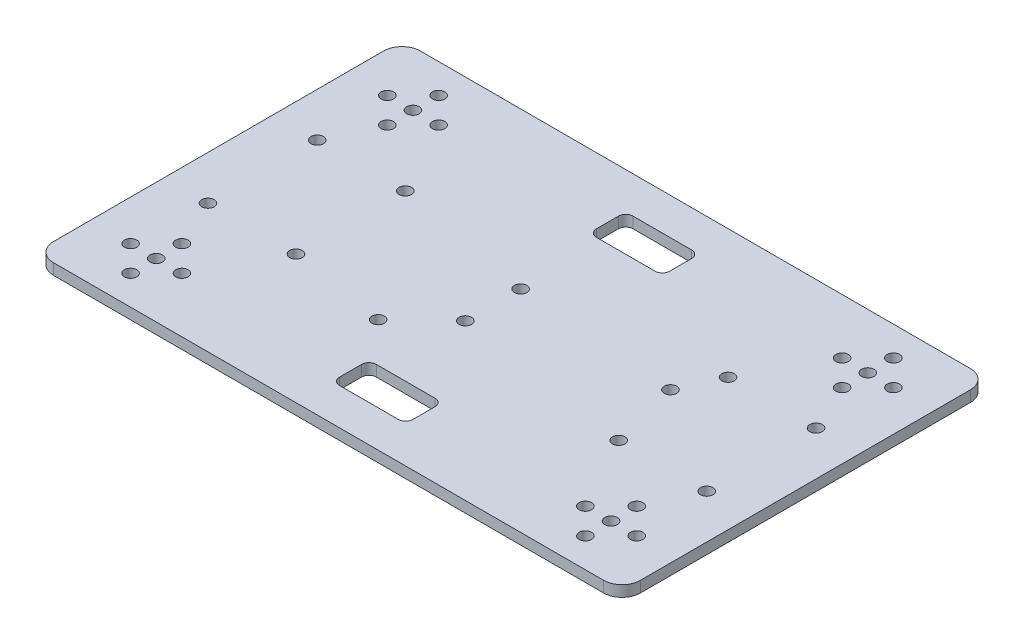
SolidWorks part; units mm, degrees
ref_plane "Front Plane" through (0, 0, 0) normal (0, 0, 1) x (1, 0, 0)
ref_plane "Top Plane" through (0, 0, 0) normal (0, 1, 0) x (1, 0, 0)
ref_plane "Right Plane" through (0, 0, 0) normal (1, 0, 0) x (0, 0, -1)
sketch "Sketch1" plane through (0, 0, 0) normal (0, 1, 0) x (1, 0, 0)
  line L1 (-80, -50) -> (80, -50)
  line L2 (-80, -50) -> (-80, 50)
  line L3 (-80, 50) -> (80, 50)
  line L4 (80, -50) -> (80, 50)
  line L5 (-80, -50) -> (80, 50) construction
  line L6 (-80, 50) -> (80, -50) construction
  point P0 (0, 0)
  dimension "D1" = 100
  dimension "D2" = 160
extrude "Boss-Extrude1" add sketch "Sketch1" along normal blind 3
sketch "Sketch3" plane through (0, 3, 0) normal (0, 1, 0) x (1, 0, 0)
  circle A0 centre (-68, 14.9) radius 1.5
  circle A1 centre (-44, 14.9) radius 1.5
  circle A2 centre (-68, -14.9) radius 1.5
  circle A3 centre (-44, -14.9) radius 1.5
  circle A4 centre (44, 14.9) radius 1.5
  circle A5 centre (68, 14.9) radius 1.5
  circle A6 centre (44, -14.9) radius 1.5
  circle A7 centre (68, -14.9) radius 1.5
  dimension "D1" = 3
  dimension "D2" = 3
  dimension "D3" = 3
  dimension "D4" = 3
  dimension "D5" = 3
  dimension "D6" = 3
  dimension "D7" = 3
  dimension "D8" = 3
hole_wizard "M3 Clearance Hole1" positions "3DSketch1" profile "Sketch4" hole size "M3" standard "ISO" end condition up to next
sketch3d "3DSketch1"
  point P0 (-68, 3, -14.9)
  point P3 (-44, 3, -14.9)
  point P6 (-68, 3, 14.9)
  point P9 (-44, 3, 14.9)
  point P12 (68, 3, -14.9)
  point P15 (44, 3, -14.9)
  point P18 (44, 3, 14.9)
  point P21 (68, 3, 14.9)
sketch "Sketch4" plane through (-68, 3, -14.9) normal (1, 0, 0) x (0, 0, 1)
  line L0 (0, 0) -> (0, 3)
  line L1 (0, 3) -> (1.7, 3)
  line L2 (1.7, 3) -> (1.7, 0)
  line L5 (1.7, 0) -> (0, 0)
  line L11 (0, -6.35) -> (0, 107.95) construction
  dimension "Thru Hole Dia." = 3.4
  dimension "Thru Hole Depth" = 3
sketch "Sketch8" plane through (0, 3, 0) normal (0, 1, 0) x (1, 0, 0)
  line L5 (-9, -30) -> (11, -30)
  line L6 (-9, -30) -> (-9, -40)
  line L7 (-9, -40) -> (11, -40)
  line L8 (11, -30) -> (11, -40)
  line L9 (-9, -30) -> (11, -40) construction
  line L10 (-9, -40) -> (11, -30) construction
  line L11 (-80, -50) -> (80, -50) construction
  line L12 (47, -22) -> (47, -48) construction
  line L13 (-80, 0) -> (80, 0) construction
  line L14 (-80, 50) -> (-80, -50) construction
  line L15 (80, -50) -> (80, 50) construction
  line L16 (-9, 40) -> (11, 30) construction
  line L17 (-9, 30) -> (11, 40) construction
  line L18 (11, 30) -> (11, 40)
  line L19 (-9, 40) -> (11, 40)
  line L20 (-9, 30) -> (-9, 40)
  line L21 (-9, 30) -> (11, 30)
  point P4 (1, -35)
  point P19 (1, 35)
  dimension "D1" = 20
  dimension "D2" = 10
  dimension "D3" = 10
  dimension "D4" = 46
extrude "Cut-Extrude1" cut sketch "Sketch8" against normal up to next
hole_wizard "M3 Clearance Hole3" positions "Sketch9" profile "Sketch10" hole size "M3" standard "ISO" end condition up to next
sketch "Sketch9" plane through (0, 3, 0) normal (0, 1, 0) x (1, 0, 0)
  point P0 (-5.121, 7.4767)
  point P3 (-5.1439, -7.5842)
sketch "Sketch10" plane through (-5.121, 3, -7.4767) normal (1, 0, 0) x (0, 0, 1)
  line L0 (0, 0) -> (0, 3)
  line L1 (0, 3) -> (1.7, 3)
  line L2 (1.7, 3) -> (1.7, 0)
  line L5 (1.7, 0) -> (0, 0)
  line L11 (0, -6.35) -> (0, 107.95) construction
  dimension "Thru Hole Dia." = 3.4
  dimension "Thru Hole Depth" = 3
hole_wizard "M3 Clearance Hole4" positions "Sketch11" profile "Sketch12" hole size "M3" standard "ISO" end condition up to next
sketch "Sketch11" plane through (0, 3, 0) normal (0, 1, 0) x (1, 0, 0)
  point P0 (-62, 35)
  point P3 (-62, 42)
  point P6 (-69, 35)
  point P9 (-62, 28)
  point P12 (-55, 35)
  point P15 (-62, -42)
  point P18 (-69, -35)
  point P21 (-62, -28)
  point P24 (-55, -35)
  point P27 (-62, -35)
  point P30 (-17.3, -19.2)
  point P33 (39.1, 4.1)
  point P36 (-5.121, 7.4767)
  point P39 (-5.1439, -7.5842)
  point P42 (62, -35)
  point P45 (69, -35)
  point P48 (62, -42)
  point P51 (55, -35)
  point P54 (62, -28)
  point P57 (69, 35)
  point P60 (62, 35)
  point P63 (62, 42)
  point P66 (55, 35)
  point P69 (62, 28)
sketch "Sketch12" plane through (-62, 3, -35) normal (1, 0, 0) x (0, 0, 1)
  line L0 (0, 0) -> (0, 3)
  line L1 (0, 3) -> (1.7, 3)
  line L2 (1.7, 3) -> (1.7, 0)
  line L5 (1.7, 0) -> (0, 0)
  line L11 (0, -6.35) -> (0, 107.95) construction
  dimension "Thru Hole Dia." = 3.4
  dimension "Thru Hole Depth" = 3
fillet "Fillet1" radius 5 4 edges at (-80, 1.5, -50) (80, 1.5, -50) (80, 1.5, 50) (-80, 1.5, 50)
fillet "Fillet2" radius 2 8 edges at (-9, 1.5, 30) (11, 1.5, 30) (11, 1.5, 40) (-9, 1.5, 40) (11, 1.5, -40) (-9, 1.5, -40) (-9, 1.5, -30) (11, 1.5, -30)
